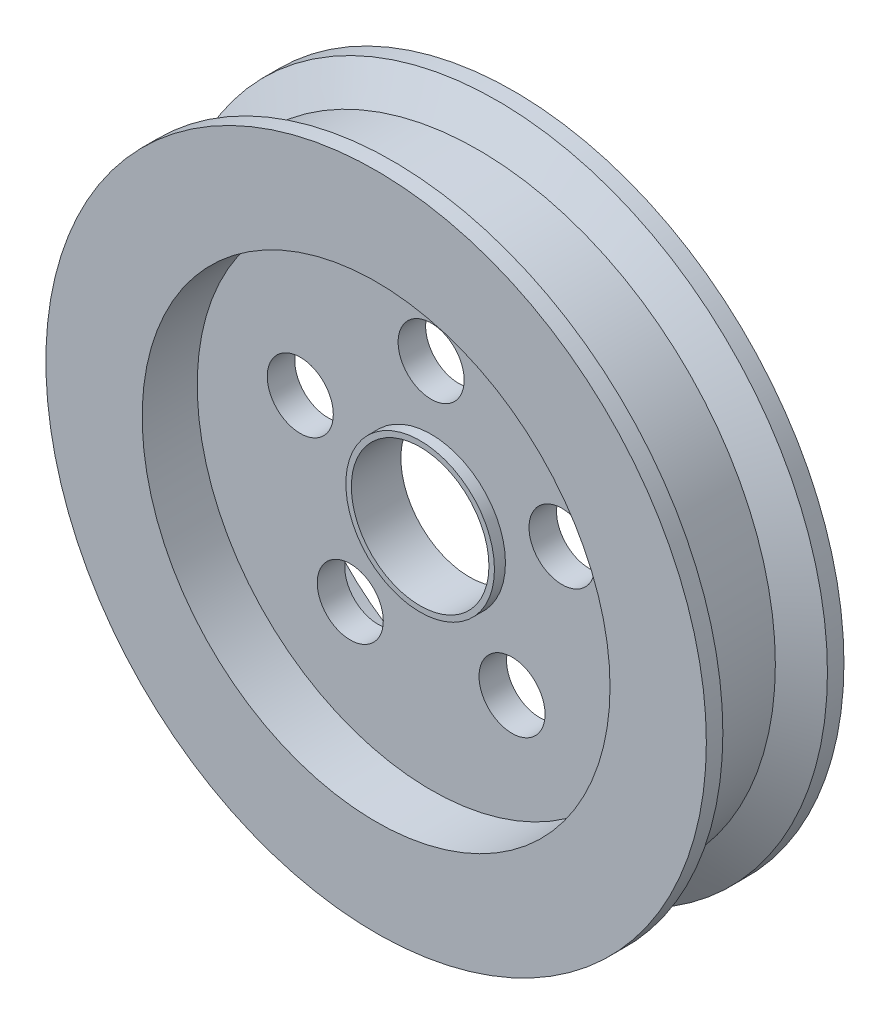
SolidWorks part; units mm, degrees
ref_plane "Front Plane" through (0, 0, 0) normal (0, 0, 1) x (1, 0, 0)
ref_plane "Top Plane" through (0, 0, 0) normal (0, 1, 0) x (1, 0, 0)
ref_plane "Right Plane" through (0, 0, 0) normal (1, 0, 0) x (0, 0, -1)
sketch "Sketch1" plane through (0, 0, 0) normal (0, 0, 1) x (1, 0, 0)
  circle A0 centre (0, 0) radius 60
  circle A1 centre (0, 0) radius 12.5
  dimension "D1" = 120
  dimension "D2" = 25
extrude "Boss-Extrude1" add sketch "Sketch1" along normal mid plane 25
sketch "Sketch2" plane through (0, 0, 12.5) normal (0, 0, 1) x (1, 0, 0)
  circle A0 centre (0, 0) radius 42.5
  dimension "D1" = 85
extrude "Cut-Extrude1" cut sketch "Sketch2" against normal blind 10
mirror "Mirror1" about plane through (0, 0, 0) normal (0, 0, 1) of "Cut-Extrude1"
sketch "Sketch3" plane through (0, 0, 2.5) normal (0, 0, 1) x (1, 0, 0)
  circle A0 centre (0, 25) radius 6
  dimension "D1" = 12
  dimension "D2" = 25
extrude "Cut-Extrude2" cut sketch "Sketch3" against normal through all
pattern_circular "CirPattern1" count 5 over 360 about axis through (0, 0, 0) along (0, 0, 1) of "Cut-Extrude2"
sketch "Sketch4" plane through (0, 0, 0) normal (0, 1, 0) x (1, 0, 0)
  line L0 (0, 0) -> (0, 31.3003) construction
  line L1 (60, 9.5) -> (54, 6.0359)
  line L2 (60, -12.5) -> (60, 12.5) construction
  line L3 (54, 6.0359) -> (54, -6.0359)
  line L4 (54, -6.0359) -> (60, -9.5)
  line L5 (60, -9.5) -> (60, 9.5)
  line L6 (60, 12.5) -> (-60, 12.5) construction
  line L7 (-60, -12.5) -> (60, -12.5) construction
  dimension "D1" = 6
  dimension "D2" = 3
  dimension "D3" = 3
  dimension "D4" = 60
  dimension "D5" = 60
  dimension "D6" = 12.0718
revolve "Cut-Revolve1" cut sketch "Sketch4" angle 360 about L0
sketch "Sketch5" plane through (0, 0, 2.5) normal (0, 0, 1) x (1, 0, 0)
  circle A0 centre (0, 0) radius 13.5
  circle A1 centre (0, 0) radius 12.5 construction
  circle A2 centre (0, 0) radius 12.5
  dimension "D1" = 27
extrude "Boss-Extrude2" add sketch "Sketch5" along normal blind 2 and the other way blind 7
